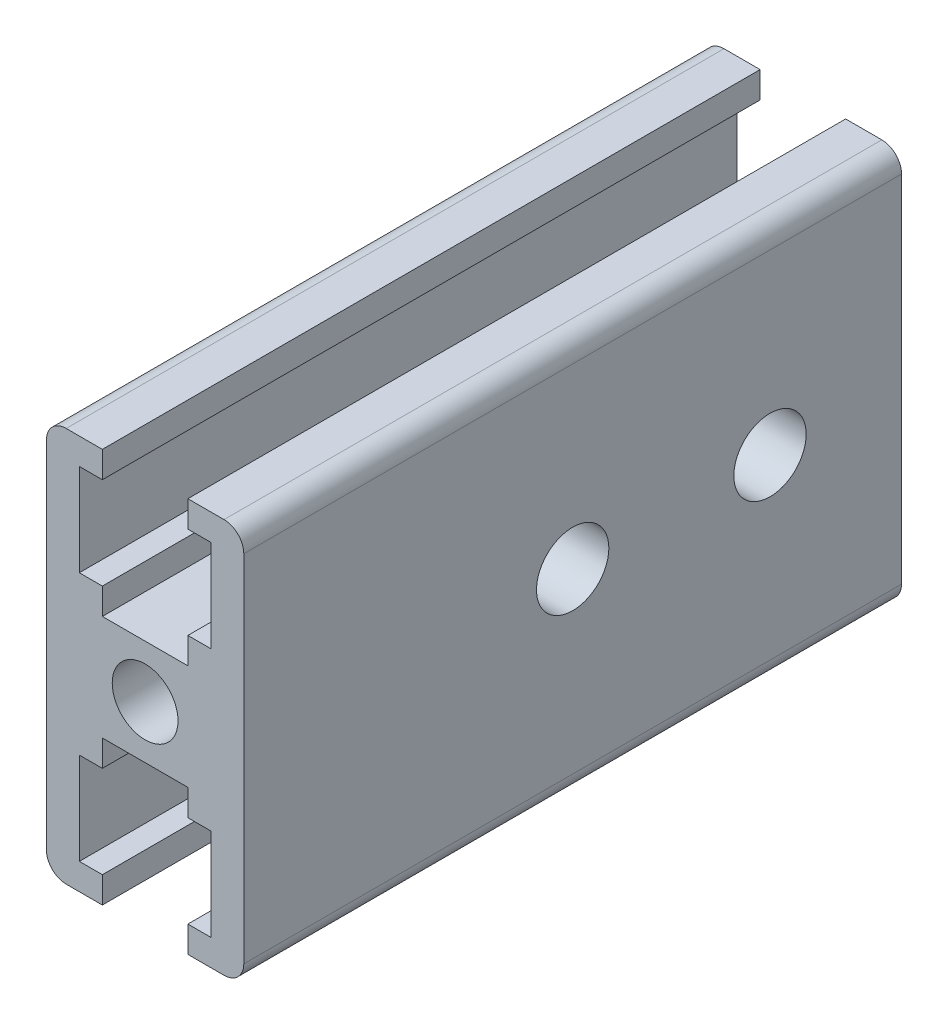
SolidWorks part; units mm, degrees
ref_plane "Plane1" through (0, 0, 0) normal (0, 0, 1) x (1, 0, 0)
ref_plane "Plane2" through (0, 0, 0) normal (0, 1, 0) x (1, 0, 0)
ref_plane "Plane3" through (0, 0, 0) normal (1, 0, 0) x (0, 0, -1)
sketch "Sketch1" plane through (0, 0, 0) normal (0, 0, 1) x (1, 0, 0)
  line L1 (0, 16.311) -> (0, -16.311) construction
  line L2 (0, 0) -> (9.513, 0) construction
  line L3 (-6, -15) -> (-3.25, -15)
  line L4 (-7.5, -13.5) -> (-7.5, 13.5)
  line L5 (-6, 15) -> (-3.25, 15)
  line L6 (7.5, -13.5) -> (7.5, 13.5)
  line L8 (-3.25, 4) -> (3.25, 4)
  line L17 (3.25, 15) -> (6, 15)
  line L18 (-3.25, 6) -> (-3.25, 4)
  line L19 (-5, 6) -> (-3.25, 6)
  line L20 (-5, 13) -> (-5, 6)
  line L21 (-3.25, 13) -> (-5, 13)
  line L22 (3.25, 6) -> (3.25, 4)
  line L23 (5, 6) -> (3.25, 6)
  line L24 (5, 13) -> (5, 6)
  line L25 (3.25, 13) -> (5, 13)
  line L26 (-3.25, 15) -> (-3.25, 13)
  line L27 (3.25, 15) -> (3.25, 13)
  line L38 (3.25, -6) -> (3.25, -4)
  line L39 (5, -6) -> (3.25, -6)
  line L40 (5, -13) -> (5, -6)
  line L41 (3.25, -13) -> (5, -13)
  line L42 (-3.25, -6) -> (-3.25, -4)
  line L43 (-5, -6) -> (-3.25, -6)
  line L44 (-5, -13) -> (-5, -6)
  line L45 (-3.25, -13) -> (-5, -13)
  line L46 (-3.25, -4) -> (3.25, -4)
  line L47 (3.25, -15) -> (3.25, -13)
  line L48 (-3.25, -15) -> (-3.25, -13)
  line L49 (3.25, -15) -> (6, -15)
  arc A0 (-6, -15) -> (-7.5, -13.5) centre (-6, -13.5) cw
  arc A1 (6, -15) -> (7.5, -13.5) centre (6, -13.5) ccw
  arc A2 (6, 15) -> (7.5, 13.5) centre (6, 13.5) cw
  arc A3 (-7.5, 13.5) -> (-6, 15) centre (-6, 13.5) cw
  circle A4 centre (0, 0) radius 2.5
  point P4 (0, 0)
  point P44 (-7.5, 15)
  point P45 (7.5, 15)
  point P46 (7.5, -15)
  point P47 (-7.5, -15)
  point P48 (0, -15)
  point P49 (0, 15)
extrude "凸台-拉伸1" add sketch "Sketch1" along normal blind 50
cosmetic thread "孔螺蚊线1" parameters "D1"=12, "D2"=6
hole_wizard "Ø5.5 (5.5) 直径孔1" positions "草图2" profile "草图1" hole size "Ø5.5" standard "Gb" end condition through all
sketch "草图2" plane through (7.5, 0, 0) normal (1, 0, 0) x (0, 0, -1)
  line L0 (-50, 15) -> (0, 15) construction
  line L1 (-50, -13.5) -> (-50, 13.5) construction
  point P0 (-25, 0)
  dimension "D1" = 15
  dimension "D2" = 25
sketch "草图1" plane through (7.5, 0, 25) normal (0, 1, 0) x (0, 0, -1)
  line L0 (0, 0) -> (0, 15)
  line L1 (0, 15) -> (2.75, 15)
  line L2 (2.75, 15) -> (2.75, 0)
  line L5 (2.75, 0) -> (0, 0)
  line L11 (0, -6.35) -> (0, 107.95) construction
  dimension "通孔孔直径" = 5.5
  dimension "通孔孔深度" = 15
sketch "草图3" plane through (7.5, 0, 0) normal (1, 0, 0) x (0, 0, -1)
  line L0 (0, -13.5) -> (0, 13.5) construction
  line L7 (-50, 15) -> (0, 15) construction
  circle A0 centre (-10, 0) radius 2.75
  point P6 (-9.1956, 15)
  point P7 (-7.538, 15)
  point P8 (-8.3747, 15)
  dimension "D1" = 10
  dimension "D2" = 15
hole_wizard "Ø5.5 (5.5) 直径孔2" positions "草图5" profile "草图4" hole size "Ø5.5" standard "Gb" end condition through all
sketch "草图5" plane through (7.5, 0, 0) normal (1, 0, 0) x (0, 0, -1)
  point P0 (-10, 0)
sketch "草图4" plane through (7.5, 0, 10) normal (0, 1, 0) x (0, 0, -1)
  line L0 (0, 0) -> (0, 15)
  line L1 (0, 15) -> (2.75, 15)
  line L2 (2.75, 15) -> (2.75, 0)
  line L5 (2.75, 0) -> (0, 0)
  line L11 (0, -6.35) -> (0, 107.95) construction
  dimension "通孔孔直径" = 5.5
  dimension "通孔孔深度" = 15
hole_wizard "M6 螺纹孔1" positions "3D草图1" profile "草图6" tap size "M6" standard "Gb"
sketch3d "3D草图1"
  line L0 (0, 0, 50) -> (0, 0, 27.75) construction
  point P0 (0, 0, 0)
  point P4 (0, 0, 50)
sketch "草图6" plane through (0, 0, 50) normal (1, 0, 0) x (0, -1, 0)
  line L0 (0, 0) -> (0, 26.5022)
  line L1 (0, 26.5022) -> (2.5, 25)
  line L2 (2.5, 25) -> (2.5, 0)
  line L5 (2.5, 0) -> (0, 0)
  line L10 (0, 26.5022) -> (-2.5, 25) construction
  line L11 (0, -6.35) -> (0, 107.95) construction
  dimension "螺纹孔钻头直径" = 5
  dimension "螺纹孔钻头深度" = 25
  dimension "导头角度" = 118
